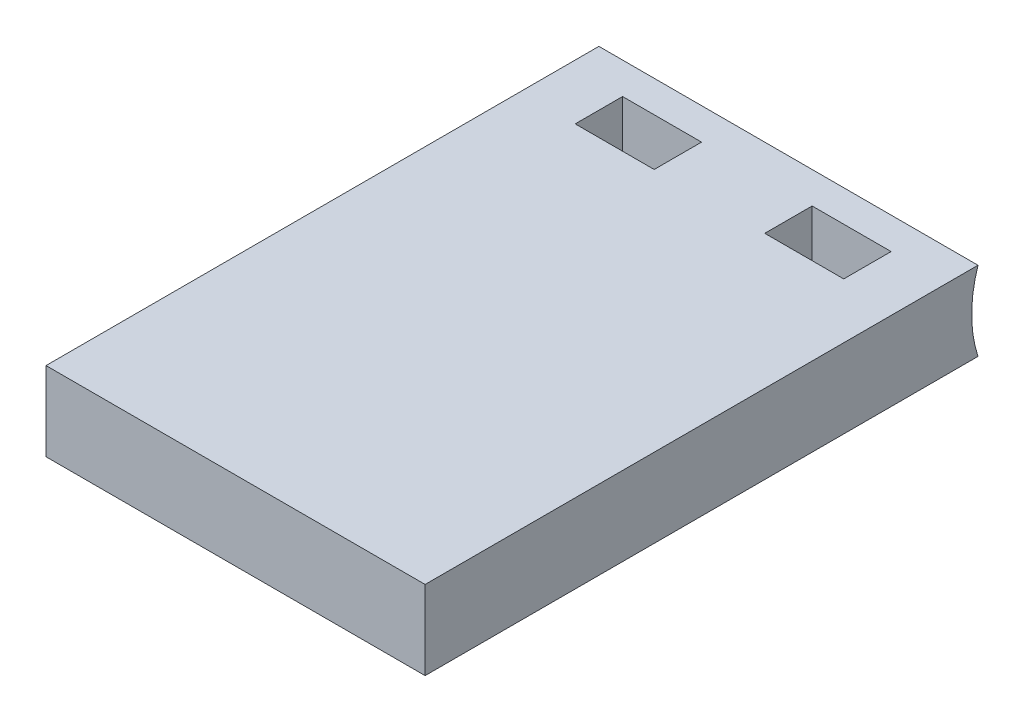
SolidWorks part; units mm, degrees
ref_plane "Piano frontale" through (0, 0, 0) normal (0, 0, 1) x (1, 0, 0)
ref_plane "Piano superiore" through (0, 0, 0) normal (0, 1, 0) x (1, 0, 0)
ref_plane "Piano destro" through (0, 0, 0) normal (1, 0, 0) x (0, 0, -1)
sketch "PiantaServomotore" plane through (0, 0, 0) normal (0, 1, 0) x (1, 0, 0)
  line L1 (12, 11) -> (-12, 11)
  line L2 (12, 11) -> (12, -11)
  line L3 (12, -11) -> (-12, -11)
  line L4 (-12, 11) -> (-12, -11)
  line L5 (12, 11) -> (-12, -11) construction
  line L6 (12, -11) -> (-12, 11) construction
  point P0 (0, 0)
  dimension "D1" = 22
  dimension "D2" = 24
sketch "Schizzo2" plane through (0, 0, 0) normal (0, 1, 0) x (1, 0, 0)
  line L1 (12, -17.5) -> (-12, -17.5)
  line L2 (12, -17.5) -> (12, 17.5)
  line L3 (12, 17.5) -> (-12, 17.5)
  line L4 (-12, -17.5) -> (-12, 17.5)
  line L5 (12, -17.5) -> (-12, 17.5) construction
  line L6 (12, 17.5) -> (-12, -17.5) construction
  point P0 (0, 0)
  dimension "D1" = 24
  dimension "D2" = 35
extrude "BaseSupporto" add sketch "Schizzo2" along normal blind 5
sketch "Schizzo3" plane through (-12, 0, 0) normal (-1, 0, 0) x (0, 0, 1)
  line L0 (-17.5, 5) -> (-17.5, 0) construction
  line L1 (-25.0993, 2.5) -> (-17.5, 2.5) construction
  circle A0 centre (-25.0993, 2.5) radius 8
  dimension "D1" = 16
extrude "AppoggioAlLongherone" cut sketch "Schizzo3" against normal through all
sketch "Schizzo4" plane through (0, 5, 0) normal (0, 1, 0) x (1, 0, 0)
  line L0 (-6, 14) -> (-12, 14) construction
  line L1 (-3.5, 12.5) -> (-8.5, 12.5)
  line L2 (-3.5, 12.5) -> (-3.5, 15.5)
  line L3 (-3.5, 15.5) -> (-8.5, 15.5)
  line L4 (-8.5, 12.5) -> (-8.5, 15.5)
  line L5 (-3.5, 12.5) -> (-8.5, 15.5) construction
  line L6 (-3.5, 15.5) -> (-8.5, 12.5) construction
  line L7 (8.5, 12.5) -> (3.5, 12.5)
  line L8 (8.5, 12.5) -> (8.5, 15.5)
  line L9 (8.5, 15.5) -> (3.5, 15.5)
  line L10 (3.5, 12.5) -> (3.5, 15.5)
  line L11 (8.5, 12.5) -> (3.5, 15.5) construction
  line L12 (8.5, 15.5) -> (3.5, 12.5) construction
  line L13 (-12, 17.5) -> (-12, -17.5) construction
  line L14 (6, 14) -> (12, 14) construction
  line L15 (12, -17.5) -> (12, 17.5) construction
  line L16 (-6, 14) -> (-6, 17.5) construction
  line L17 (12, 17.5) -> (-12, 17.5) construction
  point P0 (-6, 14)
  point P5 (6, 14)
  dimension "D1" = 3
  dimension "D2" = 5
  dimension "D3" = 6
  dimension "D4" = 3.5
extrude "ForiFascette" cut sketch "Schizzo4" against normal through all
